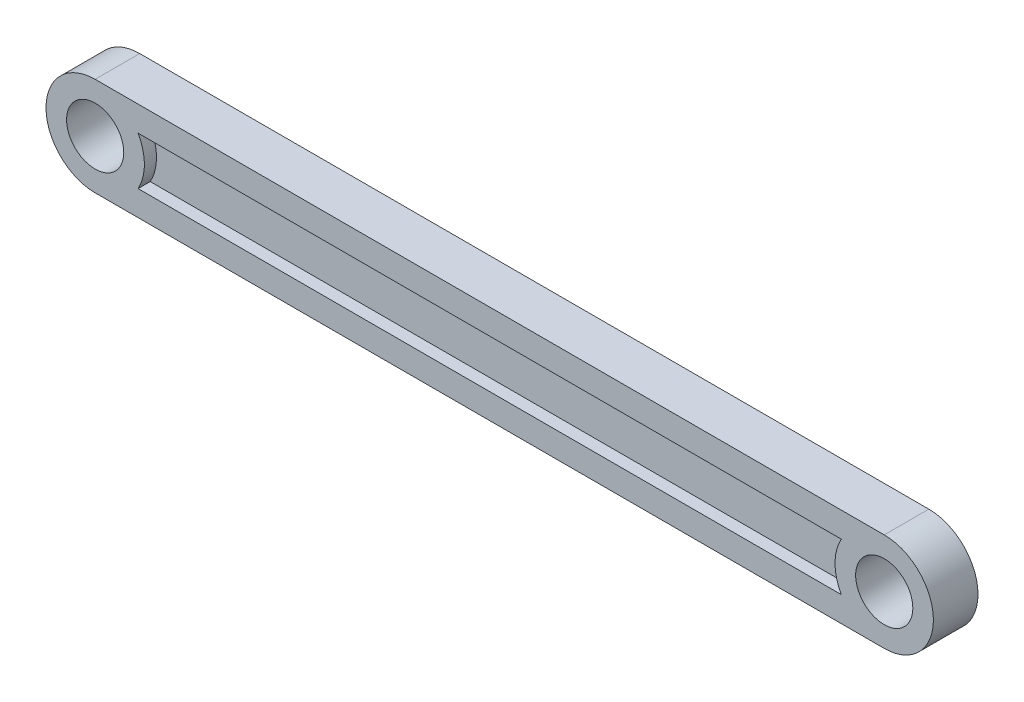
SolidWorks part; units mm, degrees
ref_plane "Front Plane" through (0, 0, 0) normal (0, 0, 1) x (1, 0, 0)
ref_plane "Top Plane" through (0, 0, 0) normal (0, 1, 0) x (1, 0, 0)
ref_plane "Right Plane" through (0, 0, 0) normal (1, 0, 0) x (0, 0, -1)
sketch "Sketch1" plane through (0, 0, 0) normal (0, 0, 1) x (1, 0, 0)
  line L0 (34.5, 0) -> (-34.5, 0) construction
  line L1 (34.5, -4.3) -> (-34.5, -4.3)
  line L2 (34.5, 4.3) -> (-34.5, 4.3)
  arc A0 (34.5, -4.3) -> (34.5, 4.3) centre (34.5, 0) ccw
  arc A1 (-34.5, 4.3) -> (-34.5, -4.3) centre (-34.5, 0) ccw
  circle A2 centre (-34.5, 0) radius 2.5
  circle A3 centre (34.5, 0) radius 2.5
  point P2 (0, 0)
  dimension "D3" = 5
  dimension "D1" = 8.6
  dimension "D2" = 69
extrude "Boss-Extrude1" add sketch "Sketch1" along normal mid plane 3.9
sketch "Sketch2" plane through (0, 0, 1.95) normal (0, 0, 1) x (1, 0, 0)
  line L0 (34.5, 2.1) -> (-34.5, 2.1)
  line L1 (-34.5, -2.1) -> (34.5, -2.1)
  line L2 (34.5, 4.3) -> (-34.5, 4.3)
  line L3 (-34.5, -4.3) -> (34.5, -4.3)
  line L4 (34.5, 4.3) -> (-34.5, 4.3)
  line L5 (-34.5, -4.3) -> (34.5, -4.3)
  arc A2 (34.5, -4.3) -> (34.5, 4.3) centre (34.5, 0) ccw
  arc A3 (-34.5, 4.3) -> (-34.5, -4.3) centre (-34.5, 0) ccw
  arc A4 (34.5, -4.3) -> (34.5, 4.3) centre (34.5, 0) ccw
  arc A5 (-34.5, 4.3) -> (-34.5, -4.3) centre (-34.5, 0) ccw
  circle A8 centre (-34.5, 0) radius 4.3
  circle A9 centre (34.5, 0) radius 4.3
  arc A10 (34.5, -2.1) -> (34.5, 2.1) centre (34.5, 0) ccw
  arc A11 (-34.5, 2.1) -> (-34.5, -2.1) centre (-34.5, 0) ccw
  dimension "D1" = 0
  dimension "D2" = 2.2
extrude "Cut-Extrude1" cut sketch "Sketch2" against normal blind 1.06 contours A9 L0 A8 L1
mirror "Mirror1" about plane through (0, 0, 0) normal (0, 0, 1) of "Cut-Extrude1"
